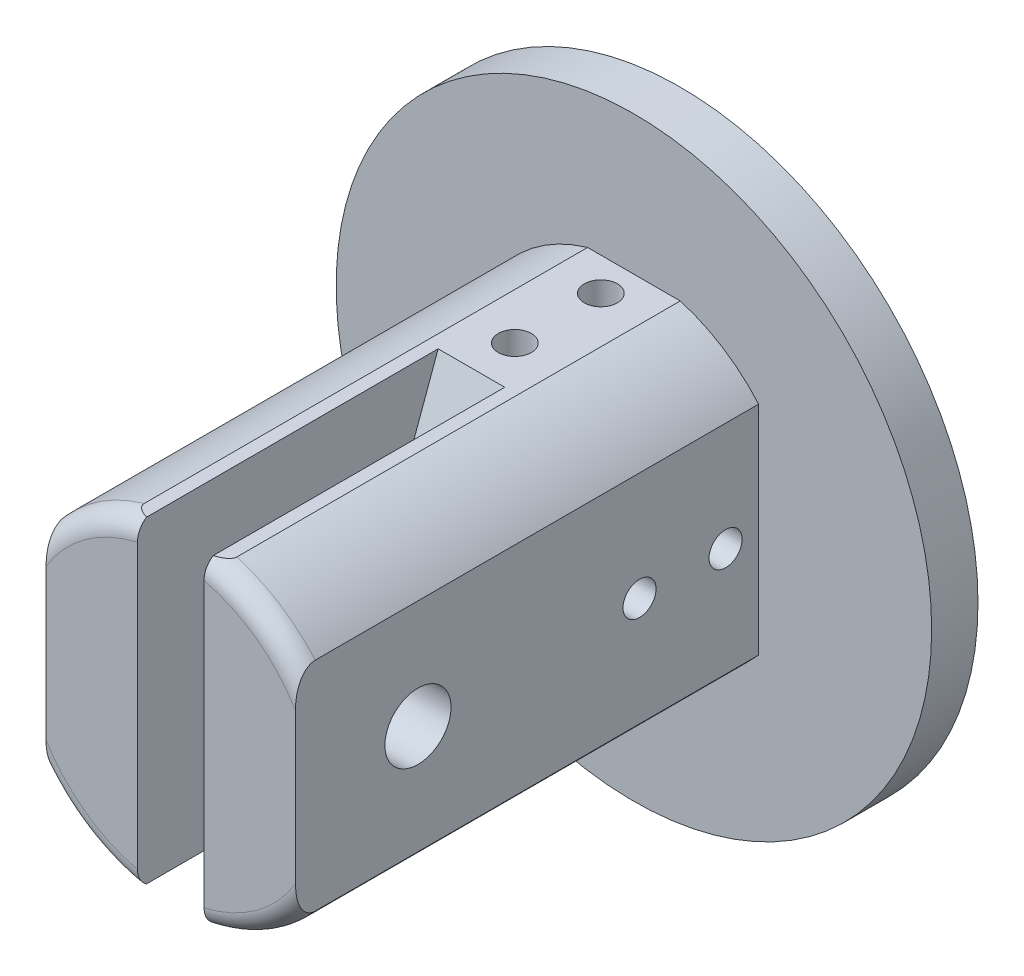
SolidWorks part; units mm, degrees
ref_plane "Спереди" through (0, 0, 0) normal (0, 0, 1) x (1, 0, 0)
ref_plane "Сверху" through (0, 0, 0) normal (0, 1, 0) x (1, 0, 0)
ref_plane "Справа" through (0, 0, 0) normal (1, 0, 0) x (0, 0, -1)
sketch "Эскиз1" plane through (0, 0, 0) normal (0, 0, 1) x (1, 0, 0)
  circle A1 centre (0, 0) radius 45
extrude "Вытянуть1" add sketch "Эскиз1" along normal blind 7
sketch "Эскиз2" plane through (0, 0, 7) normal (0, 0, 1) x (1, 0, 0)
  circle A0 centre (0, 0) radius 25
extrude "Вытянуть2" add sketch "Эскиз2" along normal blind 70
fillet "Скругление1" radius 3 1 edges at (25, 0, 77)
sketch "Эскиз3" plane through (0, 0, 0) normal (0, 1, 0) x (1, 0, 0)
  line L0 (-25, -7) -> (25, -7) construction
  circle A0 centre (0, -12) radius 2.5
  circle A1 centre (0, -25) radius 2.5
  dimension "D1" = 5
  dimension "D2" = 13
extrude "Вытянуть3" cut sketch "Эскиз3" against normal mid plane 70
sketch "Эскиз5" plane through (0, 0, 0) normal (1, 0, 0) x (0, 0, -1)
  line L0 (-7, 45) -> (-7, -45) construction
  circle A0 centre (-12, 0) radius 2.5
  circle A1 centre (-25, 0) radius 2.5
  dimension "D1" = 5
  dimension "D2" = 13
extrude "Вытянуть4" cut sketch "Эскиз5" against normal mid plane 70
sketch "Эскиз6" plane through (0, 0, 0) normal (0, 0, -1) x (-1, 0, 0)
  circle A0 centre (0, 0) radius 12.5
extrude "Вытянуть5" cut sketch "Эскиз6" against normal blind 36
sketch "Эскиз7" plane through (0, 0, 0) normal (0, 1, 0) x (1, 0, 0)
  line L0 (25, -74) -> (-25, -74) construction
  line L1 (-5.0324, -39.5546) -> (5.0324, -39.5546)
  line L2 (-5.0324, -39.5546) -> (-5.0324, -108.4454)
  line L3 (-5.0324, -108.4454) -> (5.0324, -108.4454)
  line L4 (5.0324, -39.5546) -> (5.0324, -108.4454)
  line L5 (-5.0324, -39.5546) -> (5.0324, -108.4454) construction
  line L6 (-5.0324, -108.4454) -> (5.0324, -39.5546) construction
  line L7 (0, 0) -> (0, -106.7532) construction
  line L8 (27.8494, -79.568) -> (18.8494, -79.568)
  line L9 (-27.8494, -7) -> (-18.8494, -7)
  line L10 (-27.8494, -7) -> (-27.8494, -79.568)
  line L11 (-27.8494, -79.568) -> (-18.8494, -79.568)
  line L12 (-18.8494, -7) -> (-18.8494, -79.568)
  line L13 (18.8494, -7) -> (18.8494, -79.568)
  line L14 (27.8494, -7) -> (18.8494, -7)
  line L15 (27.8494, -7) -> (27.8494, -79.568)
  line L16 (-25, -7) -> (25, -7) construction
  point P0 (0, -74)
extrude "Вытянуть6" cut sketch "Эскиз7" against normal mid plane 70
sketch "Эскиз9" plane through (0, 0, 0) normal (1, 0, 0) x (0, 0, -1)
  line L0 (0, 0) -> (30.3642, 0) construction
  line L1 (-7, 45) -> (-7, -45) construction
  line L2 (-7, 32.3741) -> (-81.4711, 32.3741)
  line L3 (-7, 32.3741) -> (-7, 24)
  line L4 (-7, 24) -> (-81.4711, 24)
  line L5 (-81.4711, 32.3741) -> (-81.4711, 24)
  line L6 (-7, -24) -> (-81.4711, -24)
  line L7 (-81.4711, -32.3741) -> (-81.4711, -24)
  line L8 (-7, -32.3741) -> (-81.4711, -32.3741)
  line L9 (-7, -32.3741) -> (-7, -24)
  dimension "D1" = 24
extrude "Вытянуть8" cut sketch "Эскиз9" against normal mid plane 70
sketch "Эскиз10" plane through (-18.8494, 0, 0) normal (-1, 0, 0) x (0, 0, 1)
  circle A0 centre (58.4863, 0) radius 5
extrude "Вырез-Вытянуть1" cut sketch "Эскиз10" against normal through all
chamfer "Фаска1" distance 8 angle 70 1 edges at (0, 24, 39.5546)
